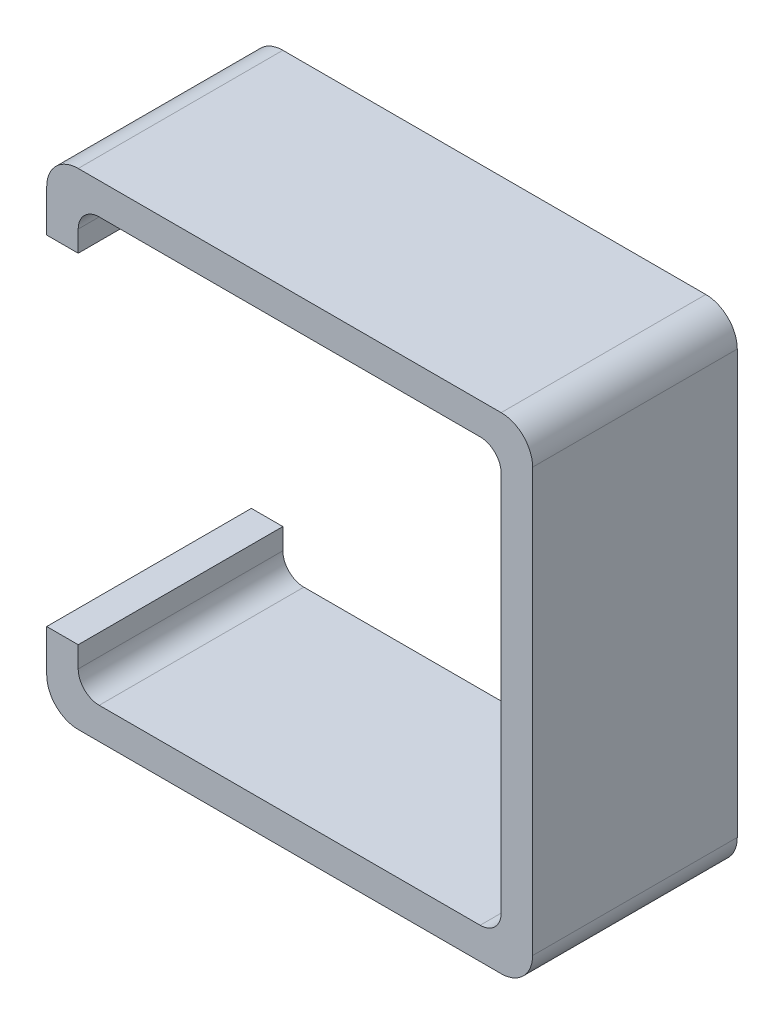
SolidWorks part; units mm, degrees
ref_plane "Front Plane" through (0, 0, 0) normal (1, 0, 0) x (0, 1, 0)
ref_plane "Top Plane" through (0, 0, 0) normal (0, 0, 1) x (0, 1, 0)
ref_plane "Right Plane" through (0, 0, 0) normal (0, 1, 0) x (-1, 0, 0)
sketch "Sketch1" plane through (0, 0, 0) normal (0, 0, 1) x (0, 1, 0)
  line L2 (8.15, 18.15) -> (8.15, 20.15)
  line L3 (5.15, 23.15) -> (1.15, 23.15)
  line L4 (1.15, 23.15) -> (1.15, 20.15)
  line L5 (1.15, 20.15) -> (3.15, 20.15)
  line L6 (5.15, 18.15) -> (5.15, -18.15)
  line L7 (3.15, -20.15) -> (-33.15, -20.15)
  line L8 (-35.15, -18.15) -> (-35.15, 18.15)
  line L9 (-33.15, 20.15) -> (-31.15, 20.15)
  line L10 (-31.15, 20.15) -> (-31.15, 23.15)
  line L11 (-31.15, 23.15) -> (-35.15, 23.15)
  line L12 (-38.15, 20.15) -> (-38.15, -20.15)
  line L13 (-35.15, -23.15) -> (5.15, -23.15)
  line L14 (8.15, -20.15) -> (8.15, 18.15)
  arc A2 (8.15, 20.15) -> (5.15, 23.15) centre (5.15, 20.15) ccw
  arc A3 (5.15, 18.15) -> (3.15, 20.15) centre (3.15, 18.15) ccw
  arc A4 (3.15, -20.15) -> (5.15, -18.15) centre (3.15, -18.15) ccw
  arc A5 (-35.15, -18.15) -> (-33.15, -20.15) centre (-33.15, -18.15) ccw
  arc A6 (-33.15, 20.15) -> (-35.15, 18.15) centre (-33.15, 18.15) ccw
  arc A7 (-35.15, 23.15) -> (-38.15, 20.15) centre (-35.15, 20.15) ccw
  arc A8 (-38.15, -20.15) -> (-35.15, -23.15) centre (-35.15, -20.15) ccw
  arc A9 (5.15, -23.15) -> (8.15, -20.15) centre (5.15, -20.15) ccw
extrude "Boss-Extrude1" add sketch "Sketch1" along normal blind 19.5
